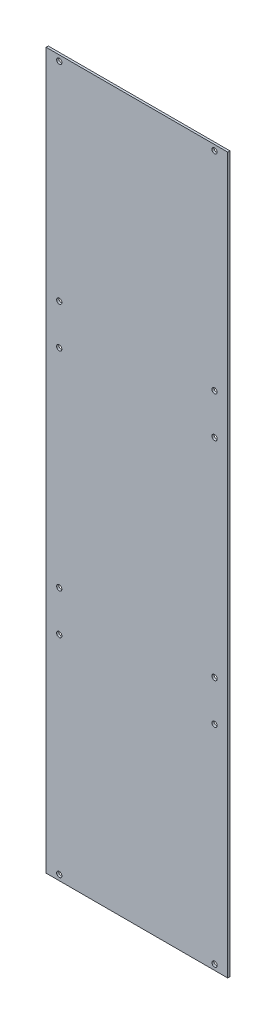
SolidWorks part; units mm, degrees
material "1100-H12 Rod (SS)"
ref_plane "Frontal" through (0, 0, 0) normal (0, 0, 1) x (1, 0, 0)
ref_plane "Superior" through (0, 0, 0) normal (0, 1, 0) x (1, 0, 0)
ref_plane "Direito" through (0, 0, 0) normal (1, 0, 0) x (0, 0, -1)
sketch "Sketch1" plane through (0, 0, 0) normal (0, 0, 1) x (1, 0, 0)
  line L1 (-41.5, -163.5) -> (41.5, -163.5)
  line L2 (-41.5, -163.5) -> (-41.5, 163.5)
  line L3 (-41.5, 163.5) -> (41.5, 163.5)
  line L4 (41.5, -163.5) -> (41.5, 163.5)
  line L5 (-41.5, -163.5) -> (41.5, 163.5) construction
  line L6 (-41.5, 163.5) -> (41.5, -163.5) construction
  point P0 (0, 0)
  dimension "D1" = 327
  dimension "D2" = 83
extrude "Boss-Extrude1" add sketch "Sketch1" along normal mid plane 1
hole_wizard "M2 Hole1 - A" positions "Sketch3" profile "Sketch2" hole size "M2" standard "DIN" end condition through all
sketch "Sketch3" plane through (0, 0, 0.5) normal (0, 0, 1) x (1, 0, 0)
  line L0 (41.5, 163.5) -> (-41.5, 163.5) construction
  line L1 (-41.5, 163.5) -> (-41.5, -163.5) construction
  line L2 (41.5, -163.5) -> (41.5, 163.5) construction
  line L3 (-41.5, -163.5) -> (41.5, -163.5) construction
  point P0 (-35.5, 161)
  point P2 (35.5, 161)
  point P4 (-35.5, 66)
  point P6 (35.5, 66)
  point P8 (-35.5, 47.5)
  point P10 (35.5, 47.5)
  point P12 (-35.5, -47.5)
  point P14 (35.5, -47.5)
  point P16 (-35.5, -66)
  point P18 (35.5, -66)
  point P20 (-35.5, -161)
  point P22 (35.5, -161)
  dimension "D1" = 2.5
  dimension "D2" = 6
  dimension "D3" = 6
  dimension "D4" = 2.5
  dimension "D5" = 95
  dimension "D6" = 18.5
  dimension "D7" = 95
  dimension "D8" = 18.5
sketch "Sketch2" plane through (-35.5, 161, 0.5) normal (1, 0, 0) x (0, -1, 0)
  line L0 (0, 0) -> (0, 1)
  line L1 (0, 1) -> (1.2, 1)
  line L2 (1.2, 1) -> (1.2, 0)
  line L5 (1.2, 0) -> (0, 0)
  line L11 (0, -6.35) -> (0, 107.95) construction
  dimension "Thru Hole Dia." = 2.4
  dimension "Thru Hole Depth" = 1
